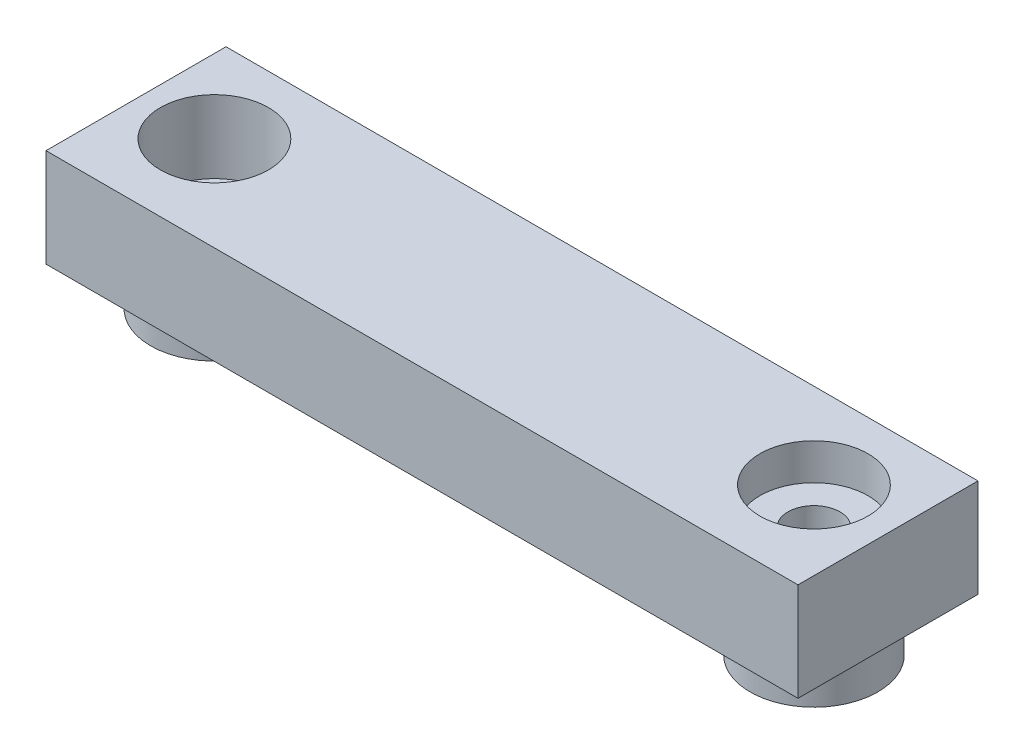
SolidWorks part; units mm, degrees
ref_plane "Alzado" through (0, 0, 0) normal (0, 0, 1) x (1, 0, 0)
ref_plane "Planta" through (0, 0, 0) normal (0, 1, 0) x (1, 0, 0)
ref_plane "Vista lateral" through (0, 0, 0) normal (1, 0, 0) x (0, 0, -1)
sketch "Croquis2" plane through (0, 0, 0) normal (0, 1, 0) x (1, 0, 0)
  line L1 (-38.0175, 33.7829) -> (38.4945, 33.7829)
  line L2 (-38.0175, 33.7829) -> (-38.0175, 15.4682)
  line L3 (-38.0175, 15.4682) -> (38.4945, 15.4682)
  line L4 (38.4945, 33.7829) -> (38.4945, 15.4682)
extrude "Saliente-Extruir1" add sketch "Croquis2" along normal blind 10
sketch "Croquis1" plane through (0, 0, 0) normal (0, 1, 0) x (1, 0, 0)
  line L0 (0, 0) -> (0, 5.3258) construction
  circle A0 centre (-30.5, 25.0866) radius 6.5
  circle A1 centre (-30.5, 25.0866) radius 2.65
  circle A2 centre (30.5, 25.0866) radius 2.65
  circle A3 centre (30.5, 25.0866) radius 6.5
  dimension "D2" = 13
  dimension "D3" = 5.3
  dimension "D1" = 30.5
extrude "Saliente-Extruir2" add sketch "Croquis1" against normal blind 5
sketch "Croquis4" plane through (0, 0, 0) normal (0, -1, 0) x (1, 0, 0)
  line L0 (0, 0) -> (0, -3.4848) construction
  circle A0 centre (-30.5, -25.0866) radius 2.5
  circle A1 centre (30.5, -25.0866) radius 2.5
extrude "Cortar-Extruir1" cut sketch "Croquis4" against normal blind 50 and the other way blind 31
hole_wizard "Refrentado para tornillo con cabeza troncocónica de M51" positions "Croquis3D1" profile "Croquis5" counterbore size "M5" standard "Ansi Metric"
sketch3d "Croquis3D1"
  line L0 (30.5, 0, -25.0866) -> (30.5, 10, -25.0866) construction
  line L1 (30.5, -5, -25.0866) -> (30.5, 0, -25.0866) construction
  line L2 (-30.5, 0, -25.0866) -> (-30.5, 10, -25.0866) construction
  point P0 (30.5, 0, -25.0866)
  point P6 (-30.5, 10, -25.0866)
  point P10 (30.5, 0, -25.0866)
sketch "Croquis5" plane through (-30.5, 10, -25.0866) normal (1, 0, 0) x (0, 0, 1)
  line L0 (0, 0) -> (0, 15)
  line L1 (0, 15) -> (2.65, 15)
  line L3 (2.65, 15) -> (2.65, 3.7)
  line L4 (2.65, 3.7) -> (5.5, 3.7)
  line L5 (5.5, 3.7) -> (5.5, 0)
  line L7 (5.5, 0) -> (0, 0)
  line L11 (0, -6.35) -> (0, 107.95) construction
  dimension "Diámetro de taladro hasta el siguiente" = 5.3
  dimension "Profundidad de taladro hasta el siguiente" = 15
  dimension "Diámetro de refrentado" = 11
  dimension "Profundidad de refrentado" = 3.7
hole_wizard "Refrentado para tornillo con cabeza troncocónica de M52" positions "Croquis3D2" profile "Croquis6" counterbore size "M5" standard "Ansi Metric" end condition through all
sketch3d "Croquis3D2"
  line L0 (-30.5, -5, -25.0866) -> (-30.5, 6.3, -25.0866) construction
  point P0 (-30.5, 6.3, -25.0866)
sketch "Croquis6" plane through (-30.5, 6.3, -25.0866) normal (1, 0, 0) x (0, 0, 1)
  line L0 (0, 0) -> (0, 11.3)
  line L1 (0, 11.3) -> (2.65, 11.3)
  line L3 (2.65, 11.3) -> (2.65, 3.7)
  line L4 (2.65, 3.7) -> (5.5, 3.7)
  line L5 (5.5, 3.7) -> (5.5, 0)
  line L7 (5.5, 0) -> (0, 0)
  line L11 (0, -6.35) -> (0, 107.95) construction
  dimension "Diámetro de taladro hasta el siguiente" = 5.3
  dimension "Profundidad de taladro hasta el siguiente" = 11.3
  dimension "Diámetro de refrentado" = 11
  dimension "Profundidad de refrentado" = 3.7
hole_wizard "Refrentado para tornillo con cabeza troncocónica de M53" positions "Croquis3D3" profile "Croquis7" counterbore size "M5" standard "Ansi Metric" end condition through all
sketch3d "Croquis3D3"
  line L0 (30.5, 0, -25.0866) -> (30.5, 10, -25.0866) construction
  point P0 (30.5, 10, -25.0866)
sketch "Croquis7" plane through (30.5, 10, -25.0866) normal (1, 0, 0) x (0, 0, 1)
  line L0 (0, 0) -> (0, 15)
  line L1 (0, 15) -> (2.65, 15)
  line L3 (2.65, 15) -> (2.65, 3.7)
  line L4 (2.65, 3.7) -> (5.5, 3.7)
  line L5 (5.5, 3.7) -> (5.5, 0)
  line L7 (5.5, 0) -> (0, 0)
  line L11 (0, -6.35) -> (0, 107.95) construction
  dimension "Diámetro de taladro hasta el siguiente" = 5.3
  dimension "Profundidad de taladro hasta el siguiente" = 15
  dimension "Diámetro de refrentado" = 11
  dimension "Profundidad de refrentado" = 3.7
